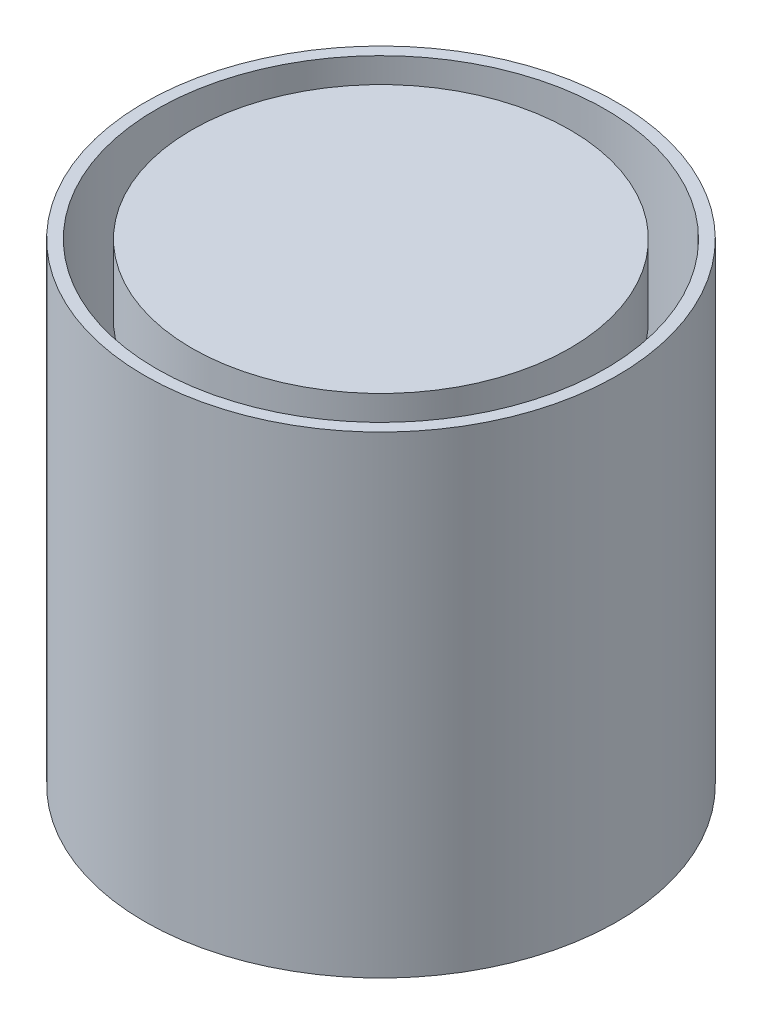
SolidWorks part; units mm, degrees
other "标注1"
sketch "草图5" plane through (100, 100, 200) normal (0.461, 0.308, 0.8323) x (-0.7479, 0.6396, 0.1776)
material "1060 合金"
ref_plane "前视基准面" through (0, 0, 0) normal (0, 0, 1) x (1, 0, 0)
ref_plane "上视基准面" through (0, 0, 0) normal (0, 1, 0) x (1, 0, 0)
ref_plane "右视基准面" through (0, 0, 0) normal (1, 0, 0) x (0, 0, -1)
other "Configuration Table"
sketch "草图6" plane through (0, 0, 0) normal (0, 1, 0) x (1, 0, 0)
  circle A0 centre (0, 0) radius 100
  circle A2 centre (0, 0) radius 95
extrude "凸台-拉伸1" add sketch "草图6" against normal blind 200
sketch "草图7" plane through (0, 0, 0) normal (0, 1, 0) x (1, 0, 0)
  circle A0 centre (0, 0) radius 80
extrude "凸台-拉伸2" add sketch "草图7" against normal blind 30 separate body
